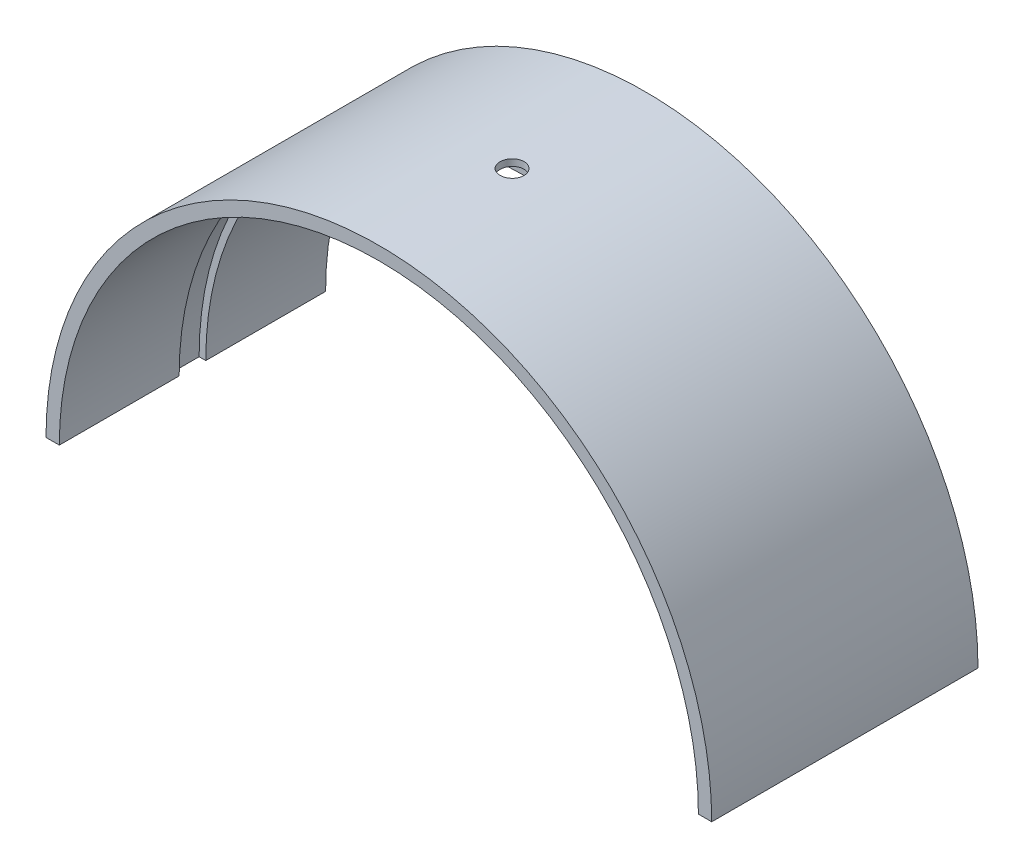
SolidWorks part; units mm, degrees
ref_plane "Ebene vorne" through (0, 0, 0) normal (0, 0, 1) x (1, 0, 0)
ref_plane "Ebene oben" through (0, 0, 0) normal (0, 1, 0) x (1, 0, 0)
ref_plane "Ebene rechts" through (0, 0, 0) normal (1, 0, 0) x (0, 0, -1)
sketch "Sketch1" plane through (0, 0, 0) normal (0, 0, 1) x (1, 0, 0)
  line L2 (24, 0) -> (25, 0)
  line L4 (-25, 0) -> (-24, 0)
  line L6 (-26, -1) -> (-23.9792, -1) construction
  line L7 (-26, 0) -> (-25, 0) construction
  line L8 (25, 0) -> (26, 0) construction
  line L9 (23.9792, -1) -> (26, -1) construction
  arc A0 (25, 0) -> (-25, 0) centre (0, 0) ccw
  arc A2 (24, 0) -> (-24, 0) centre (0, 0) ccw
  arc A4 (23.9792, -1) -> (-23.9792, -1) centre (0, 0) ccw construction
  point P1 (40.3561, 0)
  point P3 (0, 0)
  point P7 (37.6364, 11.5066)
  dimension "D1" = 50
  dimension "D2" = 1
extrude "Boss-Extrude1" add sketch "Sketch1" along normal blind 20
sketch "Sketch5" plane through (0, 0, 0) normal (0, -1, 0) x (-1, 0, 0)
  line L0 (24, -20) -> (24, 0) construction
  line L1 (24.5, -9) -> (24, -9)
  line L2 (24.5, -9) -> (24.5, -11)
  line L3 (24.5, -11) -> (24, -11)
  line L4 (24, -9) -> (24, -11)
  line L5 (0, 0) -> (0, -5.142) construction
  point P6 (24, -10)
  dimension "D1" = 2
  dimension "D2" = 0.5
  dimension "D3" = 10
revolve "Cut-Revolve2" cut sketch "Sketch5" angle 360 about L5
sketch "Sketch8" plane through (0, 0, 0) normal (0, -1, 0) x (1, 0, 0)
  line L0 (-24.5, 10) -> (3.6389, 10) construction
  line L1 (-24.5, 11) -> (-24.5, 9) construction
  line L2 (0, 0) -> (0, 10) construction
  circle A0 centre (0, 10) radius 0.9
extrude "Cut-Extrude1" cut sketch "Sketch8" against normal through all
